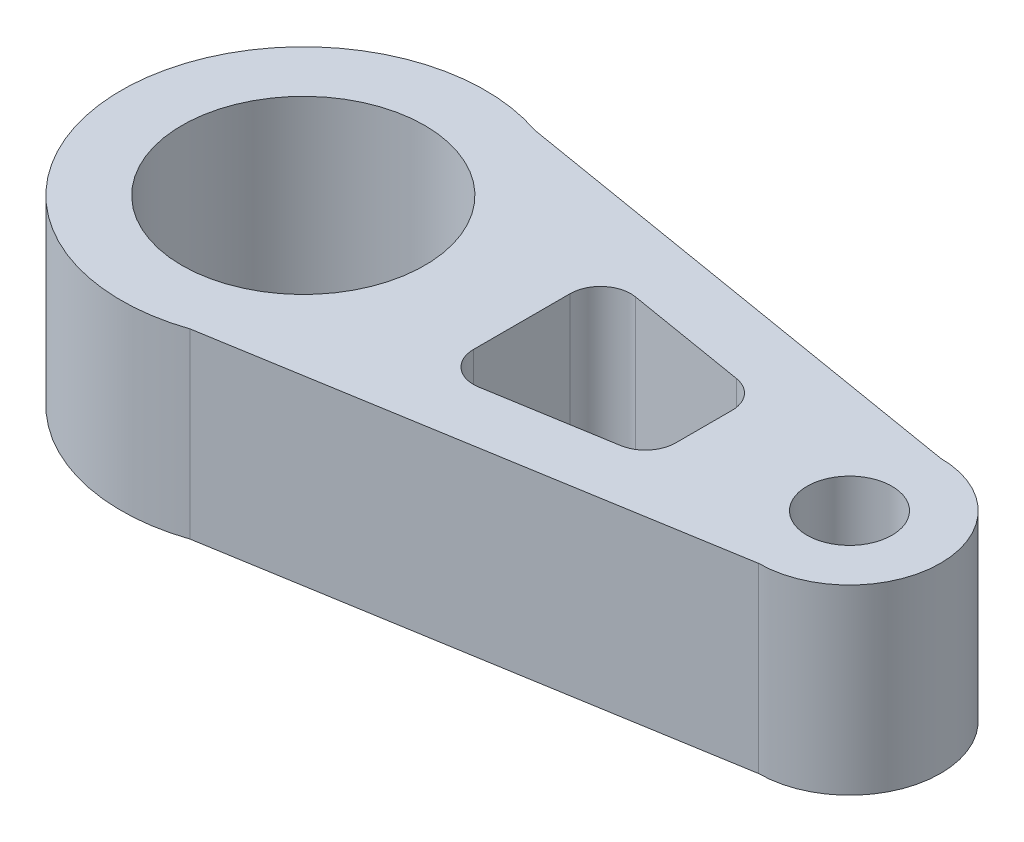
SolidWorks part; units mm, degrees
ref_plane "Front Plane" through (0, 0, 0) normal (0, 0, 1) x (1, 0, 0)
ref_plane "Top Plane" through (0, 0, 0) normal (0, 1, 0) x (1, 0, 0)
ref_plane "Right Plane" through (0, 0, 0) normal (1, 0, 0) x (0, 0, -1)
sketch "Sketch1" plane through (0, 0, 0) normal (0, 1, 0) x (1, 0, 0)
  line L0 (-61.1779, 0) -> (185.7673, 0) construction
  line L1 (0, -19.05) -> (57.15, -9.525)
  line L2 (57.15, 9.525) -> (0, 19.05)
  line L3 (22.86, 5.0544) -> (22.86, -5.0544)
  line L4 (41.91, 2.9378) -> (41.91, -2.9378)
  line L5 (39.257, -6.0696) -> (26.557, -8.1862)
  line L6 (26.557, 8.1862) -> (39.257, 6.0696)
  line L7 (57.15, -23.2696) -> (57.15, 42.6363) construction
  circle A0 centre (0, 0) radius 12.7
  circle A1 centre (57.15, 0) radius 4.445
  circle A2 centre (57.15, 0) radius 9.525
  circle A3 centre (0, 0) radius 19.05
  arc A4 (22.86, 5.0544) -> (26.557, 8.1862) centre (26.035, 5.0544) cw
  arc A5 (22.86, -5.0544) -> (26.557, -8.1862) centre (26.035, -5.0544) ccw
  arc A6 (41.91, -2.9378) -> (39.257, -6.0696) centre (38.735, -2.9378) cw
  arc A7 (41.91, 2.9378) -> (39.257, 6.0696) centre (38.735, 2.9378) ccw
  point P19 (22.86, 8.8024)
  point P22 (22.86, -8.8024)
  point P25 (41.91, -5.6274)
  point P28 (41.91, 5.6274)
  dimension "D1" = 25.4
  dimension "D2" = 38.1
  dimension "D3" = 8.89
  dimension "D4" = 19.05
  dimension "D9" = 3.175
  dimension "D5" = 57.15
  dimension "D6" = 19.05
  dimension "D7" = 19.05
  dimension "D8" = 15.24
  dimension "D10" = 6.35
  dimension "D11" = 6.35
extrude "Boss-Extrude2" add sketch "Sketch1" along normal blind 19.05 contours A3 L1 A2 L2 A7 L4 A6 L5 A5 L3 A4 L6 | A2 A1 | A0
